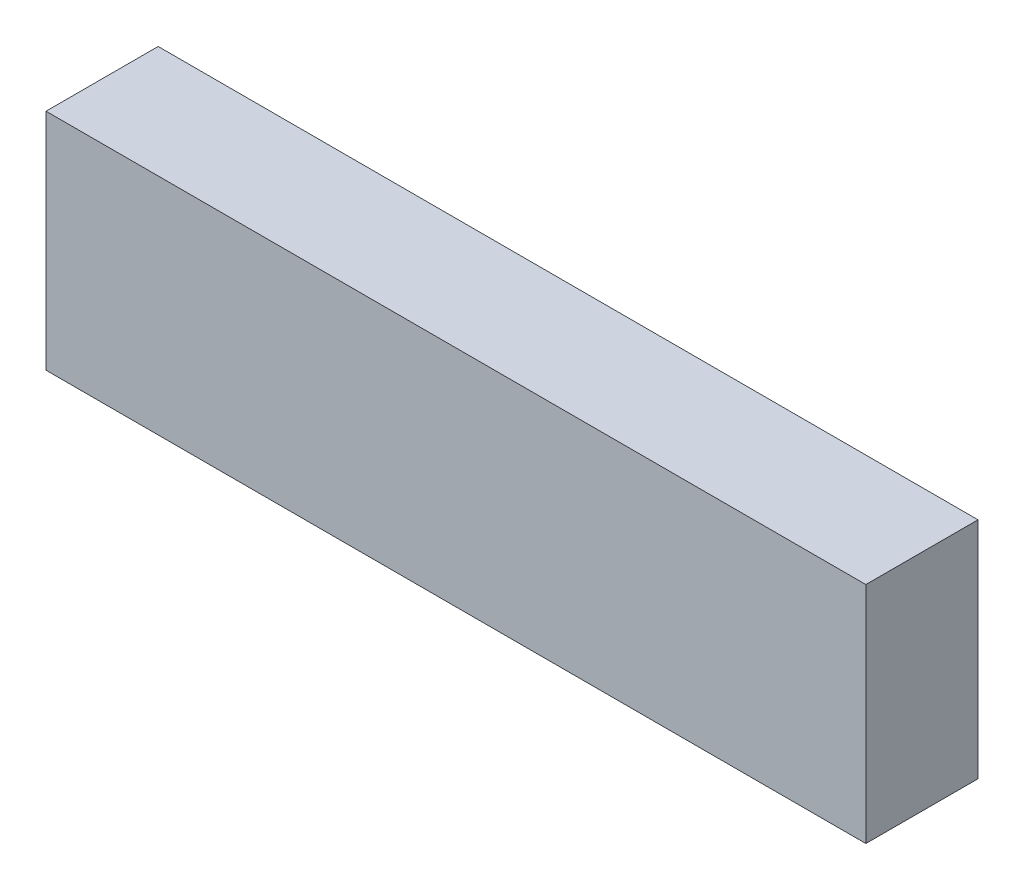
SolidWorks part; units mm, degrees
ref_plane "Front Plane" through (0, 0, 0) normal (0, 0, 1) x (1, 0, 0)
ref_plane "Top Plane" through (0, 0, 0) normal (0, 1, 0) x (1, 0, 0)
ref_plane "Right Plane" through (0, 0, 0) normal (1, 0, 0) x (0, 0, -1)
sketch "Sketch1" plane through (0, 0, 0) normal (0, 0, 1) x (1, 0, 0)
  line L1 (0, 0) -> (73.1, 0)
  line L2 (0, 0) -> (0, 20)
  line L3 (0, 20) -> (73.1, 20)
  line L4 (73.1, 0) -> (73.1, 20)
extrude "Boss-Extrude1" add sketch "Sketch1" along normal blind 10
